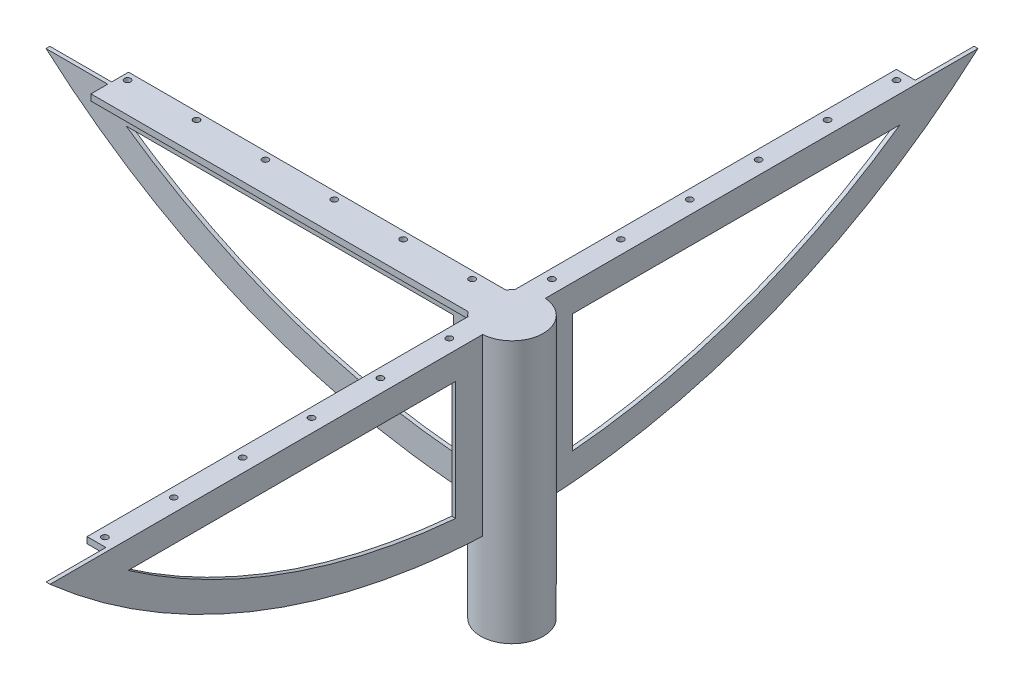
SolidWorks part; units mm, degrees
material "Stainless Steel 2205"
ref_plane "Front Plane" through (0, 0, 0) normal (0, 0, 1) x (1, 0, 0)
ref_plane "Top Plane" through (0, 0, 0) normal (0, 1, 0) x (1, 0, 0)
ref_plane "Right Plane" through (0, 0, 0) normal (1, 0, 0) x (0, 0, -1)
sketch "Sketch1" plane through (0, 0, 0) normal (0, 0, 1) x (1, 0, 0)
  line L0 (0, 0) -> (0, 1120) construction
  line L1 (740.8104, 280) -> (0, 280)
  line L2 (0, 0) -> (0, 280)
  arc A0 (0, 0) -> (740.8104, 280) centre (0, 1120) ccw
  dimension "D1" = 1120
  dimension "D2" = 280
revolve "Revolve1" add sketch "Sketch1" angle 360 about L0
sketch "Sketch4" plane through (0, 280, 0) normal (0, 1, 0) x (1, 0, 0)
  line L0 (0, -50) -> (0, -771.3201)
  line L1 (0, 50) -> (0, 771.3201)
  line L2 (-50, 0) -> (-771.3201, 0)
  line L3 (-3.175, -49.8991) -> (-3.175, -771.3201)
  line L4 (3.175, -49.8991) -> (3.175, -771.3201)
  line L5 (-49.9115, 2.9729) -> (-771.3201, 2.9729)
  line L6 (-49.8969, -3.2095) -> (-771.3201, -3.2095)
  line L7 (3.175, 49.8991) -> (3.175, 771.3201)
  line L8 (-3.175, 49.8991) -> (-3.175, 771.3201)
  line L9 (-50, 2.9729) -> (-771.3201, 2.9729) construction
  line L10 (-50, -3.2095) -> (-771.3201, -3.2095) construction
  line L11 (-3.175, 50) -> (-3.175, 771.3201) construction
  line L12 (3.175, 50) -> (3.175, 771.3201) construction
  line L13 (-3.175, -50) -> (-3.175, -771.3201) construction
  line L14 (3.175, -50) -> (3.175, -771.3201) construction
  circle A0 centre (0, 0) radius 50
  circle A1 centre (0, 0) radius 771.3201
  circle M6 centre (0, 0) radius 740.8104
  dimension "D1" = 100
  dimension "D2" = 1542.6401
extrude "Cut-Extrude1" cut sketch "Sketch4" against normal through all contours A0 L6 L3 M6 | A0 L4 L7 M6 | A0 L8 L5 M6
sketch "Sketch5" plane through (3.175, 0, 0) normal (1, 0, 0) x (0, 0, -1)
  line L0 (616.0717, 236.825) -> (93.0741, 236.825)
  line L1 (93.0741, 236.825) -> (93.0741, 47.2094)
  line L2 (740.8036, 280) -> (49.8991, 280)
  line L3 (49.8991, 280) -> (49.8991, 1.1166)
  line L4 (740.8036, 280) -> (49.8991, 280)
  line L5 (49.8991, 280) -> (49.8991, 1.1166)
  line L6 (0, 0) -> (0, 315.6143) construction
  arc A0 (93.0741, 47.2094) -> (616.0717, 236.825) centre (0, 1120) ccw
  arc A1 (49.8991, 1.1166) -> (740.8036, 280) centre (0, 1120) ccw
  arc A2 (49.8991, 1.1166) -> (740.8036, 280) centre (0, 1120) ccw
  dimension "D2" = 43.175
  dimension "D1" = 0
revolve "Cut-Revolve1" cut sketch "Sketch5" angle 360 about L6
sketch "Sketch6" plane through (0, 280, 0) normal (0, 1, 0) x (1, 0, 0)
  line L0 (-33.175, 30) -> (-33.175, -30)
  line L2 (-3.175, 646.9035) -> (-3.175, 49.8991)
  line L4 (-33.175, 646.9035) -> (-33.175, 30)
  line L6 (-3.175, -49.8991) -> (-3.175, -645.2545)
  line L7 (-3.175, -645.2545) -> (-33.175, -645.2545)
  line L8 (-33.175, -30) -> (-33.175, -645.2545)
  line L9 (-36.7252, -30) -> (-642.2296, -30)
  line L10 (-3.175, -49.8991) -> (-3.175, 49.8991)
  line L11 (-36.7252, 30) -> (-642.2296, 30)
  line L12 (-642.2296, -30) -> (-642.2296, 30)
  line L13 (-36.7252, 30) -> (-36.7252, -30)
  line L14 (-33.175, 646.9035) -> (-3.175, 646.9035)
  point P20 (-36.7252, 0)
  dimension "D2" = 60
  dimension "D3" = 30
extrude "Boss-Extrude1" add sketch "Sketch6" against normal blind 10
sketch "Sketch7" plane through (0, 280, 0) normal (0, 1, 0) x (1, 0, 0)
  line L0 (-3.175, 646.9035) -> (-33.175, 646.9035) construction
  line L1 (0, 0) -> (233.2078, 0) construction
  line L2 (0, 0) -> (-18.175, -81.9035) construction
  line L3 (-33.175, 646.9035) -> (-33.175, 37.4088) construction
  line L4 (0, 0) -> (-82.0786, 0) construction
  line L5 (0, 0) -> (-81.9035, 18.175) construction
  circle A0 centre (-18.175, 631.9035) radius 5
  circle A1 centre (-18.175, 521.9035) radius 5
  circle A2 centre (-18.175, 411.9035) radius 5
  circle A3 centre (-18.175, 301.9035) radius 5
  circle A4 centre (-18.175, 191.9035) radius 5
  circle A5 centre (-18.175, 81.9035) radius 5
  circle A6 centre (-18.175, -81.9035) radius 5
  circle A7 centre (-18.175, -191.9035) radius 5
  circle A8 centre (-18.175, -301.9035) radius 5
  circle A9 centre (-18.175, -411.9035) radius 5
  circle A10 centre (-18.175, -521.9035) radius 5
  circle A11 centre (-18.175, -631.9035) radius 5
  circle A12 centre (-81.9035, 18.175) radius 5
  circle A13 centre (-191.9035, 18.175) radius 5
  circle A14 centre (-301.9035, 18.175) radius 5
  circle A15 centre (-411.9035, 18.175) radius 5
  circle A16 centre (-521.9035, 18.175) radius 5
  circle A17 centre (-631.9035, 18.175) radius 5
  point P4 (0, 0)
  dimension "D4" = 10
  dimension "D1" = 15
  dimension "D2" = 15
  dimension "D5" = 90
  dimension "D3" = 6
extrude "Cut-Extrude2" cut sketch "Sketch7" against normal blind 33.175
sketch "Sketch8" plane through (0, 0, 0) normal (0, 0, 1) x (1, 0, 0)
  line L1 (50, 1.1166) -> (-49.8969, 1.1166)
  line L2 (50, 1.1166) -> (50, -48.9865)
  line L3 (50, -48.9865) -> (-49.8969, -48.9865)
  line L4 (-49.8969, 1.1166) -> (-49.8969, -48.9865)
extrude "Cut-Extrude3" cut sketch "Sketch8" against normal through all both and the other way through all
sketch "Sketch9" plane through (0, 1.1166, 0) normal (0, -1, 0) x (1, 0, 0)
  circle A0 centre (0, 0) radius 50
extrude "Boss-Extrude2" add sketch "Sketch9" along normal blind 140
equation "\"hatchHoleDiameter\"=600mm"
equation "\"hullThickness\"=177.1mm"
equation "\"gasketHullInterconnectWidth\"=100mm"
equation "\"collarThickness\"=20mm"
equation "\"hatchTunnelLength\"=200mm"
equation "\"oRingDiameter\"=2mm"
equation "\"boltPatternRadiusInterconnect\"=500mm"
equation "\"interconnectBoltDiameter\"=30mm"
equation "\"hatchShaftDiameter\"=20mm"
equation "\"hatchMinima\"=39.9mm"
equation "\"hullDiameter\"=2240mm"
equation "\"hatchMaxima\"=180mm"
equation "\"bushingFlatHatch\"=15mm"
equation "\"hingePivotDiameter\"=20mm"
equation "\"handleWidth\"=250mm"
equation "\"handleHeight\"=160mm"
equation "\"handleThickness\"=25mm"
equation "\"FrameLength\"=2600mm"
equation "\"FrameMidLength\"=1800mm"
equation "\"TubeOD\"=100mm"
equation "\"FrameBackFlat\"=500mm"
equation "\"TubeWall\"=15.0001mm"
equation "\"TopMemberAngle\"=140deg"
equation "\"FrameHight\"=2500mm"
equation "\"D1@Sketch1\"=\"hullDiameter\"/2"
equation "\"D2@Sketch1\"=\"hullDiameter\"/8"
equation "\"D1@Sketch4\"=\"TubeOD\""
